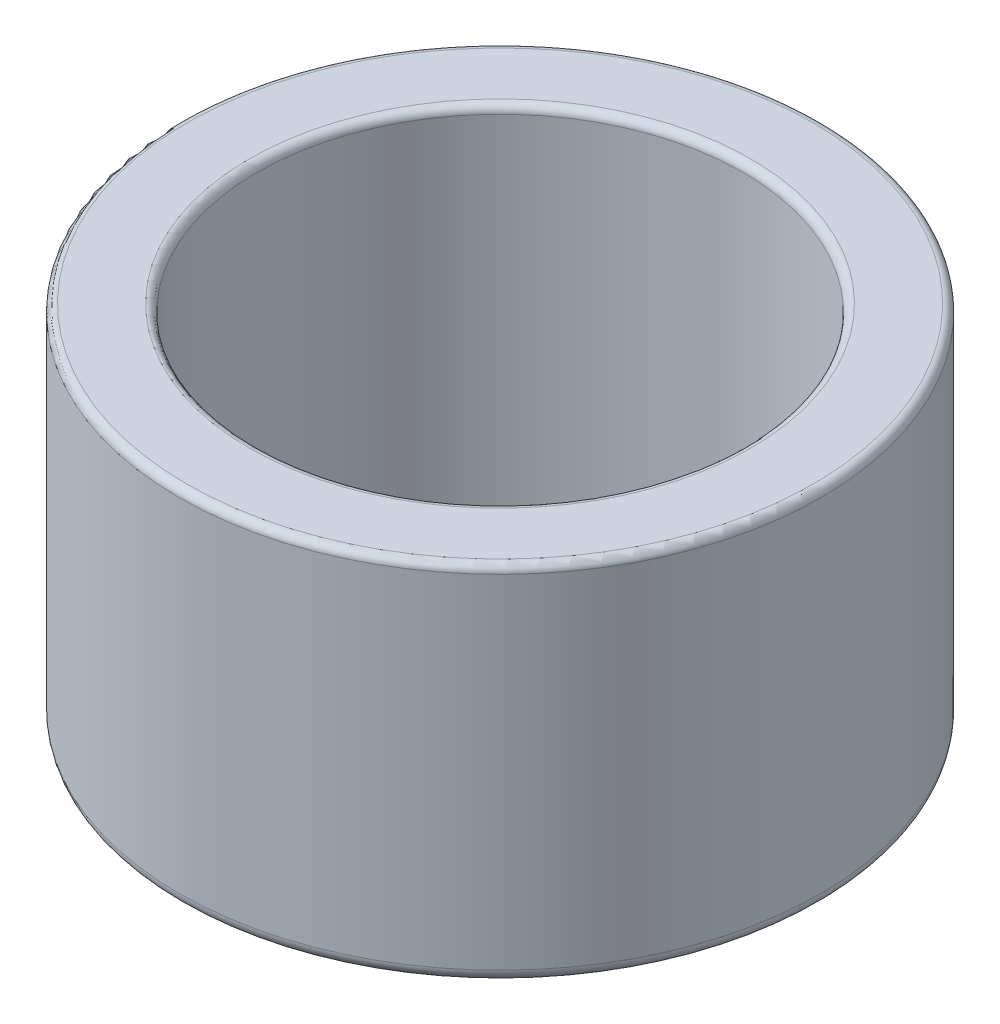
SolidWorks part; units mm, degrees
ref_plane "Front Plane" through (0, 0, 0) normal (0, 0, 1) x (1, 0, 0)
ref_plane "Top Plane" through (0, 0, 0) normal (0, 1, 0) x (1, 0, 0)
ref_plane "Right Plane" through (0, 0, 0) normal (1, 0, 0) x (0, 0, -1)
sketch "Sketch1" plane through (0, 0, 0) normal (0, 1, 0) x (1, 0, 0)
  circle A0 centre (0, 0) radius 9.3504
  circle A1 centre (0, 0) radius 12.3503
  dimension "D1" = 18.7007
  dimension "D2" = 3
extrude "Boss-Extrude1" add sketch "Sketch1" along normal blind 14
fillet "Fillet1" radius 0.3 1 edges at (0, 14, 12.3503)
fillet "Fillet5" radius 0.3 1 edges at (0, 14, 9.3504)
fillet "Fillet6" radius 0.5 1 edges at (0, 0, 12.3503)
fillet "Fillet7" radius 0.5 1 edges at (0, 0, 9.3504)
